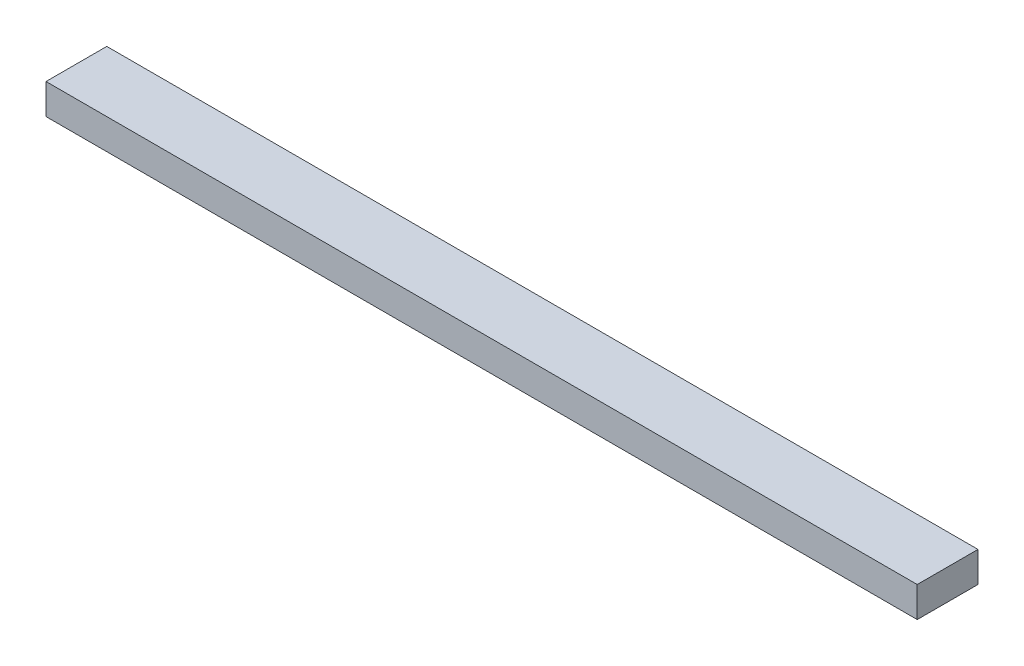
SolidWorks part; units mm, degrees
ref_plane "Front Plane" through (0, 0, 0) normal (0, 0, 1) x (1, 0, 0)
ref_plane "Top Plane" through (0, 0, 0) normal (0, 1, 0) x (1, 0, 0)
ref_plane "Right Plane" through (0, 0, 0) normal (1, 0, 0) x (0, 0, -1)
sketch "Sketch1" plane through (0, 0, 0) normal (0, 0, 1) x (1, 0, 0)
  line L0 (273.05, -152.4) -> (273.05, 152.4) construction
  line L1 (-273.05, 152.4) -> (273.05, 152.4)
  line L2 (-273.05, 152.4) -> (-273.05, 133.35)
  line L3 (-273.05, 133.35) -> (273.05, 133.35)
  line L4 (273.05, 152.4) -> (273.05, 133.35)
  dimension "D1" = 19.05
extrude "Boss-Extrude1" add sketch "Sketch1" along normal blind 38.1
